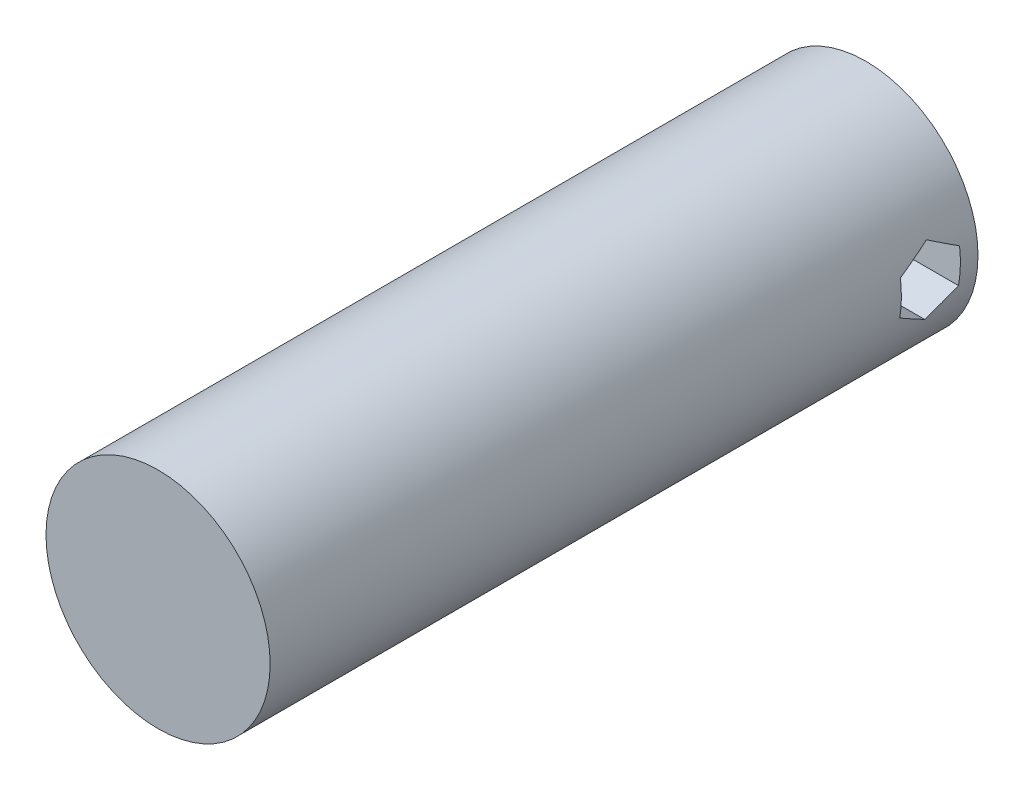
SolidWorks part; units mm, degrees
ref_plane "Front Plane" through (0, 0, 0) normal (0, 0, 1) x (1, 0, 0)
ref_plane "Top Plane" through (0, 0, 0) normal (0, 1, 0) x (1, 0, 0)
ref_plane "Right Plane" through (0, 0, 0) normal (1, 0, 0) x (0, 0, -1)
sketch "Sketch1" plane through (0, 0, 0) normal (0, 0, 1) x (1, 0, 0)
  circle A0 centre (0, 0) radius 4.75
  dimension "D1" = 9.5
extrude "Boss-Extrude1" add sketch "Sketch1" along normal blind 30
sketch "Sketch2" plane through (0, 0, 0) normal (0, 0, -1) x (-1, 0, 0)
  line L0 (1.8, 0) -> (-0.94, 0) construction
  line L1 (-0.94, 1.5351) -> (-0.94, -1.5351)
  arc A0 (-0.94, -1.5351) -> (-0.94, 1.5351) centre (0, 0) ccw
  point P7 (-0.94, 0)
  dimension "D1" = 3.6
  dimension "D2" = 2.74
extrude "Cut-Extrude1" cut sketch "Sketch2" against normal blind 10
sketch "Sketch3" plane through (0.94, 0, 0) normal (-1, 0, 0) x (0, 0, 1)
  line L0 (0, 1.5351) -> (0, -1.5351) construction
  line L1 (3.2307, 0.7541) -> (1.9623, 1.4429)
  line L2 (1.9623, 1.4429) -> (0.7316, 0.6888)
  line L3 (0.7316, 0.6888) -> (0.7693, -0.7541)
  line L4 (0.7693, -0.7541) -> (2.0377, -1.4429)
  line L5 (2.0377, -1.4429) -> (3.2684, -0.6888)
  line L6 (3.2684, -0.6888) -> (3.2307, 0.7541)
  line L8 (0, 0) -> (2, 0) construction
  circle A1 centre (2, 0) radius 1.25 construction
  dimension "D1" = 2.5
  dimension "D2" = 2
  dimension "D3" = 1.4429
extrude "Cut-Extrude2" cut sketch "Sketch3" against normal through all
